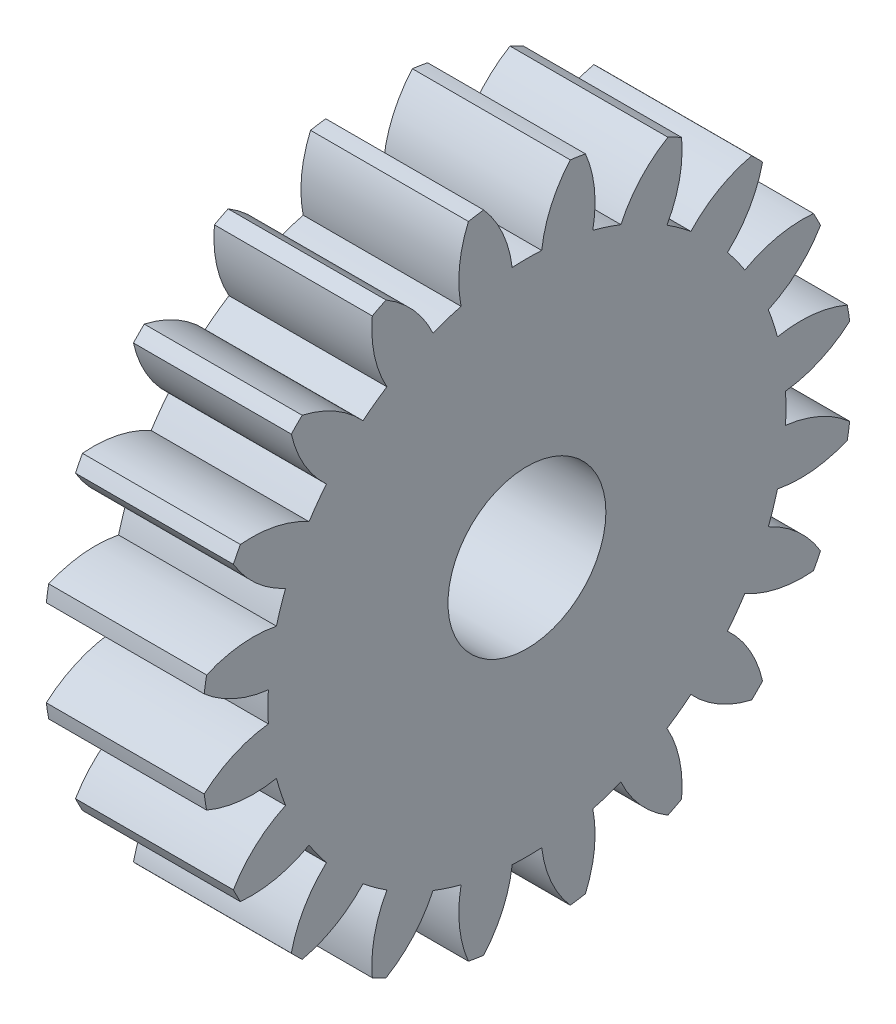
SolidWorks part; units mm, degrees
ref_plane "Plane1" through (0, 0, 0) normal (0, 0, 1) x (1, 0, 0)
ref_plane "Plane2" through (0, 0, 0) normal (0, 1, 0) x (1, 0, 0)
ref_plane "Plane3" through (0, 0, 0) normal (1, 0, 0) x (0, 0, -1)
sketch "HoldingSke" plane through (0, 0, 0) normal (0, 1, 0) x (1, 0, 0)
  line L0 (0, 0) -> (0.8353, -0.304)
  line L1 (-15, 0) -> (100, 0) construction
  line L2 (0, 0) -> (-2.1039, 2.3779)
  line L3 (0, 0) -> (-11.863, 4.5341)
  line L4 (0, 0) -> (8.1152, 2.9537)
  line L5 (0, 0) -> (-46.8476, -17.4728)
  line L6 (0, 0) -> (-4.9738, -3.3558)
  line L7 (-2.1039, 2.3779) -> (8.6586, 51.2059)
  line L8 (-76.2, 54.61) -> (-75.2, 54.61)
  line L9 (-71.009, 38.7566) -> (-53.1078, 45.2721)
  line L10 (-76.2, 71.12) -> (104.1128, 71.12)
  line L11 (0, 0) -> (-6, 0)
  line L12 (-76.2, 101.6) -> (-76.158, 101.6)
  line L13 (24.9733, 27.94) -> (52.9518, 28.4284)
  line L14 (24.9733, 27.94) -> (24.9743, 27.94)
  line L15 (24.9733, 27.94) -> (100.4006, 29.5858)
  line L16 (-63.627, -1.125) -> (-12.827, -1.125)
  circle A0 centre (0, 0) radius 3
  circle A1 centre (0, 0) radius 9.8427
  circle A2 centre (0, 0) radius 37.5
  circle A3 centre (0, 0) radius 3
  dimension "Hub_dia" = 75
  dimension "Bore" = 6
  dimension "MBD" = 6
  dimension "Num_teeth" = 20
  dimension "Overall_len" = 50
  dimension "Show_teeth" = 20
  dimension "Thickness" = 6
  dimension "OAL" = 50.0001
  dimension "T_dim" = 1
  dimension "Ap" = 20
  dimension "H" = 19.05
  dimension "Pitch_radius" = 180.3128
  dimension "Width" = 6
  dimension "Addendum_fac" = 1
  dimension "Dedendum_fac" = 1.25
  dimension "Clearance_fac" = 0.25
  dimension "Dedendum_add" = 0.001
sketch "BasProSke" plane through (0, 0, 0) normal (0, 1, 0) x (1, 0, 0)
  line L0 (-10, 0) -> (60, 0) construction
  line L1 (0, 0) -> (0, 12.375)
  line L2 (0, 0) -> (6, 0)
  line L3 (6, 0) -> (6, 12.375)
  line L4 (6, 12.375) -> (0, 12.375)
  dimension "Thickness" = 6
revolve "Base-Revolve" add sketch "BasProSke" angle 360 about L0
sketch "TooCutSke" plane through (0, 0, 0) normal (1, 0, 0) x (0, 0, -1)
  line L1 (0, 0) -> (0, 107) construction
  line L2 (0, 0) -> (-0.9561, 11.2093) construction
  line L3 (0, 0) -> (-3.5107, 22.1654) construction
  line L4 (-0.9561, 11.2093) -> (-1.7553, 11.0827) construction
  arc A0 (0.5613, 9.8267) -> (-0.5613, 9.8267) centre (0, 0) ccw
  arc A1 (1.6669, 12.2879) -> (-1.6669, 12.2879) centre (0, 0) ccw
  circle A2 centre (0, 0) radius 11.25 construction
  circle A3 centre (0, 0) radius 10.5715 construction
  arc A4 (-0.5613, 9.8267) -> (-1.6669, 12.2879) centre (-5.0301, 9.2981) ccw
  arc A5 (1.6669, 12.2879) -> (0.5613, 9.8267) centre (5.0301, 9.2981) ccw
  dimension "Flank_rad" = 4.5
  dimension "Half_ang" = 9
extrude "ToothCut" cut sketch "TooCutSke" along normal through all
fillet "Breaks" [suppressed] radius 0.0225
fillet "RootFillets" [suppressed] radius 0.2823
pattern_circular "TeethCuts" count 20 over 360 about axis through (0, 0, 0) along (1, 0, 0) of "ToothCut", "RootFillets", "Breaks"
sketch "HubNeaOneSke" plane through (0, 0, 0) normal (-1, 0, 0) x (0, 0, 1)
  circle A0 centre (0, 0) radius 9.8427
extrude "HubNearOne" [suppressed] add sketch "HubNeaOneSke" along normal blind 44.0001
sketch "HubNeaBotSke" plane through (0, 0, 0) normal (-1, 0, 0) x (0, 0, 1)
  circle A0 centre (0, 0) radius 9.8427
extrude "HubNearBoth" [suppressed] add sketch "HubNeaBotSke" along normal blind 22
ref_plane "FarPln" through (6, 0, 0) normal (1, 0, 0) x (0, 0, -1)
sketch "HubFarSke" plane through (6, 0, 0) normal (1, 0, 0) x (0, 0, -1)
  circle A0 centre (0, 0) radius 9.8427
extrude "HubFar" [suppressed] add sketch "HubFarSke" along normal blind 22
sketch "BorSke" plane through (0, 0, 0) normal (1, 0, 0) x (0, 0, -1)
  circle A0 centre (0, 0) radius 3
  dimension "Diameter" = 6
extrude "Bore" cut sketch "BorSke" along normal mid plane 100.0001
sketch "KeySke" plane through (0, 0, 0) normal (1, 0, 0) x (0, 0, -1)
  line L0 (-1, 0) -> (-1, 4)
  line L1 (-1, 4) -> (1, 4)
  line L2 (1, 4) -> (1, 0)
  line L3 (0, 0) -> (0, 34) construction
  line L4 (-1, 0) -> (1, 0)
  dimension "Offset" = 4
  dimension "Width" = 2
extrude "Keyway" [suppressed] cut sketch "KeySke" along normal mid plane 100.0001
pattern_circular "Keyway2" [suppressed] count 2 every 90 about axis through (-10, 0, 0) along (1, 0, 0)
sketch "Sketch1" plane through (6, 0, 0) normal (1, 0, 0) x (0, 0, -1)
  circle A0 centre (0, 0) radius 3 construction
  circle A1 centre (0, 0) radius 3
extrude "Boss-Extrude1" add sketch "Sketch1" against normal up to surface (6 mm away) up to face at (0, 0, -3)
sketch "Sketch2" plane through (6, 0, 0) normal (1, 0, 0) x (0, 0, -1)
  line L0 (-1.8, 2.0125) -> (-1.8, -2.0125)
  line L1 (1.8, 2.0125) -> (1.8, -2.0125)
  line L2 (-1.8, 0) -> (1.8, 0) construction
  circle A0 centre (0, 0) radius 2.7
  point P9 (0, 0)
  dimension "D1" = 5.4
  dimension "D2" = 3.6
extrude "Cut-Extrude1" cut sketch "Sketch2" against normal up to surface (6 mm away) contours L0 L2 L1 A0 | L2 L0 A0 L1 up to face at (0, 0, 0)
sketch "Sketch3" plane through (6, 0, 0) normal (1, 0, 0) x (0, 0, -1)
  circle A0 centre (0, 0) radius 3
  dimension "D1" = 6
extrude "Cut-Extrude2" cut sketch "Sketch3" against normal up to surface (6 mm away) up to face at (0, 0, 0)
equation "' \"Module@HoldingSke\" = 6.35"
equation "' \"Num_teeth@HoldingSke\" = 12"
equation "' \"Ap@HoldingSke\" =  20"
equation "' \"Ap@HoldingSke\" = 20"
equation "' \"Width@HoldingSke\" = 0.5 * 25.4"
equation "' \"Hub_dia@HoldingSke\"= 1 * 25.4"
equation "' \"Hub_dia@HoldingSke\" = 1 * 25.4"
equation "' \"Overall_len@HoldingSke\" = 1.0 * 25.4"
equation "' \"Bore@HoldingSke\" = 0.75 * 25.4"
equation "' \"T_dim@HoldingSke\" = 0.1 * 25.4"
equation "' \"Width@KeySke\" = 0.25 * 25.4"
equation "' \"Show_teeth@HoldingSke\" = 13"
equation "' \"Backlash@HoldingSke\" = 0.009 * 25.4"
equation "' \"Addendum_fac@HoldingSke\" = 1.0"
equation "' \"Dedendum_fac@HoldingSke\" = 1.25"
equation "' \"Dedendum_add@HoldingSke\" = 0.00005 * 25.4"
equation "' \"Clearance_fac@HoldingSke\" = 0.25"
equation "\"Pitch@HoldingSke\" = 1 / \"Module@HoldingSke\""
equation "\"Overcut_dia@TooCutSke\" = (\"Num_teeth@HoldingSke\" + 2 * \"Addendum_fac@HoldingSke\") / \"Pitch@HoldingSke\" + 0.002 * 25.4"
equation "\"Pitch_dia@TooCutSke\" = \"Num_teeth@HoldingSke\" / \"Pitch@HoldingSke\""
equation "\"Base_dia@TooCutSke\" = \"Num_teeth@HoldingSke\" / \"Pitch@HoldingSke\" * cos((\"Ap@HoldingSke\"  * 3.14159265 / 180))"
equation "\"Root_dia@TooCutSke\" = (\"Num_teeth@HoldingSke\" + 2) / \"Pitch@HoldingSke\" - 2 * (\"Addendum_fac@HoldingSke\" + \"Dedendum_fac@HoldingSke\") / \"Pitch@HoldingSke\" - \"Dedendum_add@HoldingSke\" * 2"
equation "\"Half_ang@TooCutSke\" = 180 / \"Num_teeth@HoldingSke\""
equation "\"Half_CT@TooCutSke\" = \"Num_teeth@HoldingSke\" / \"Pitch@HoldingSke\" * sin((3.14159265 / 2 / \"Num_teeth@HoldingSke\")) / 2 - 7 * \"Backlash@HoldingSke\" / 4"
equation "\"Flank_rad@TooCutSke\" = \"Num_teeth@HoldingSke\" / \"Pitch@HoldingSke\" / 5"
equation "\"Radius@RootFillets\" = \"Clearance_fac@HoldingSke\" / \"Pitch@HoldingSke\" + \"Dedendum_add@HoldingSke\""
equation "\"Break_rad@Breaks\" = 0.02 / \"Pitch@HoldingSke\""
equation "\"Thickness@HoldingSke\" = \"Width@HoldingSke\""
equation "\"OAL@HoldingSke\" = \"Thickness@HoldingSke\""
equation "\"MHD@HoldingSke\" = (\"Num_teeth@HoldingSke\" + 2) / \"Pitch@HoldingSke\" - 2 * (\"Addendum_fac@HoldingSke\" + \"Dedendum_fac@HoldingSke\")  / \"Pitch@HoldingSke\" - \"Dedendum_add@HoldingSke\" * 2"
equation "\"MBD@HoldingSke\" = (\"Num_teeth@HoldingSke\" + 2) / \"Pitch@HoldingSke\" - 2 * (\"Addendum_fac@HoldingSke\" + \"Dedendum_fac@HoldingSke\")  / \"Pitch@HoldingSke\" - \"Dedendum_add@HoldingSke\" * 2 - 0.002 * 25.4"
equation "\"MHD@HoldingSke\" = ((sgn( \"MHD@HoldingSke\" - \"Hub_dia@HoldingSke\" )-1)*( \"MHD@HoldingSke\" - \"Hub_dia@HoldingSke\" ))/-2+ \"Hub_dia@HoldingSke\""
equation "\"MBD@HoldingSke\" = ((sgn( \"MBD@HoldingSke\" - \"Bore@HoldingSke\" )-1)*( \"MBD@HoldingSke\" - \"Bore@HoldingSke\" ))/-2+ \"Bore@HoldingSke\""
equation "\"OAL@HoldingSke\" = ((sgn( \"OAL@HoldingSke\" - \"Overall_len@HoldingSke\" )+1)*( \"OAL@HoldingSke\" - \"Overall_len@HoldingSke\" ))/2 + \"Overall_len@HoldingSke\" + 0.000002 * 25.4"
equation "\"Num_teeth@TeethCuts\" = int( \"Show_teeth@HoldingSke\" ) + 1"
equation "\"Num_teeth@TeethCuts\" = ((sgn( \"Num_teeth@TeethCuts\" - \"Num_teeth@HoldingSke\" )-1)*( \"Num_teeth@TeethCuts\" - \"Num_teeth@HoldingSke\" ))/-2+ \"Num_teeth@HoldingSke\""
equation "\"Num_teeth@TeethCuts\" = ((sgn( \"Num_teeth@TeethCuts\" - 2.0)+1)*( \"Num_teeth@TeethCuts\" - 2.0))/2 +2.0"
equation "\"Angle@TeethCuts\" = 360.0 / \"Num_teeth@HoldingSke\""
equation "\"Diameter@BasProSke\" = (\"Num_teeth@HoldingSke\" + 2 * \"Addendum_fac@HoldingSke\") / \"Pitch@HoldingSke\""
equation "\"Thickness@BasProSke\"  = \"Thickness@HoldingSke\""
equation "' \"Fillet_rad@BasProSke\" =  \"Thickness@HoldingSke\" * 0.05"
equation "' \"Fillet_rad@BasProSke\" = \"Thickness@HoldingSke\" * 0.05"
equation "\"MHD@HoldingSke\" = ((sgn( \"MHD@HoldingSke\" - \"Root_dia@TooCutSke\" )-1)*( \"MHD@HoldingSke\" - \"Root_dia@TooCutSke\" ))/-2+ \"Root_dia@TooCutSke\""
equation "\"Diameter@HubNeaOneSke\" = \"MHD@HoldingSke\""
equation "\"Length@HubNearOne\" = \"OAL@HoldingSke\" - \"Thickness@BasProSke\""
equation "\"Diameter@HubNeaBotSke\" = \"MHD@HoldingSke\""
equation "\"Length@HubNearBoth\" = ( \"OAL@HoldingSke\" - \"Thickness@BasProSke\" ) / 2.0"
equation "\"Thickness@FarPln\" = \"Thickness@BasProSke\""
equation "\"Diameter@HubFarSke\" = \"MHD@HoldingSke\""
equation "\"Length@HubFar\" = ( \"OAL@HoldingSke\" - \"Thickness@BasProSke\" ) / 2.0"
equation "\"Diameter@BorSke\" = \"MBD@HoldingSke\""
equation "\"D1@Bore\" = \"OAL@HoldingSke\" * 2.0"
equation "\"D1@Keyway\" = \"OAL@HoldingSke\" * 2.0"
equation "\"Offset@KeySke\" = \"T_dim@HoldingSke\" + \"MBD@HoldingSke\" / 2.0"
